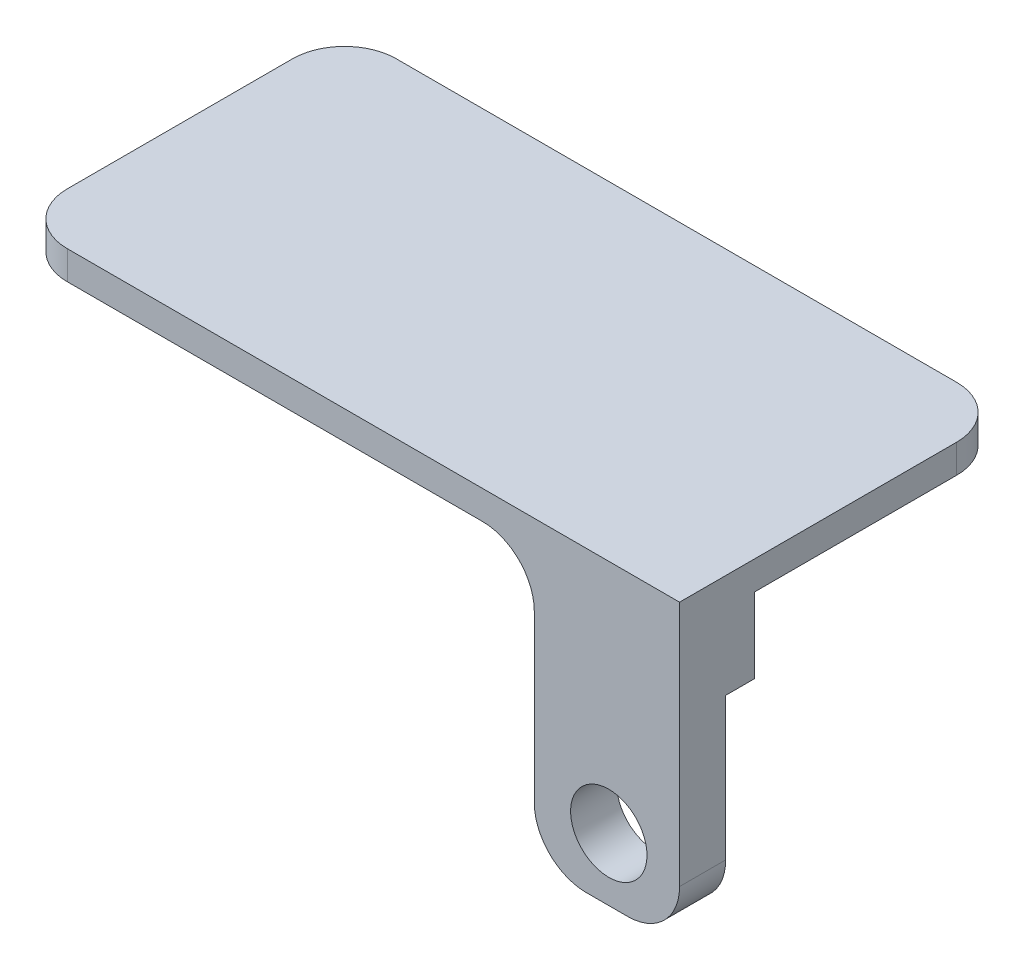
SolidWorks part; units mm, degrees
ref_plane "Front Plane" through (0, 0, 0) normal (0, 0, 1) x (1, 0, 0)
ref_plane "Top Plane" through (0, 0, 0) normal (0, 1, 0) x (1, 0, 0)
ref_plane "Right Plane" through (0, 0, 0) normal (1, 0, 0) x (0, 0, -1)
sketch "Sketch7" plane through (0, 0, 44.4916) normal (1, 0, 0) x (0, 1, 0)
  line L0 (57.2443, -80.0524) -> (75.9783, -80.0524)
  line L1 (83.2164, -82.8415) -> (83.2164, -107.3106)
  line L2 (75.9783, -80.0524) -> (75.9783, -82.8415)
  line L3 (85.9783, -75.6081) -> (57.2443, -75.6081)
  line L4 (57.2443, -80.0524) -> (57.2443, -75.6081)
  line L5 (83.2164, -107.3106) -> (85.9783, -107.3106)
  line L6 (85.9783, -107.3106) -> (85.9783, -75.6081)
  line L7 (75.9783, -82.8415) -> (83.2164, -82.8415)
  dimension "D1" = 10
extrude "Boss-Extrude6" add sketch "Sketch7" against normal blind 14
sketch "Sketch8" plane through (0, 0, -31.1164) normal (0, 0, 1) x (1, 0, 0)
  line L1 (-14, 75.9783) -> (0, 75.9783) construction
  circle A0 centre (-6.8193, 63.2783) radius 3.68
  dimension "D1" = 12.7
extrude "Cut-Extrude1" cut sketch "Sketch8" against normal blind 10
sketch "Sketch10" plane through (-14, 0, 0) normal (-1, 0, 0) x (0, 0, 1)
  line L1 (-31.1164, 85.9783) -> (-62.8189, 85.9783)
  line L2 (-31.1164, 85.9783) -> (-31.1164, 83.2164)
  line L3 (-31.1164, 83.2164) -> (-62.8189, 83.2164)
  line L4 (-62.8189, 85.9783) -> (-62.8189, 83.2164)
extrude "Boss-Extrude8" add sketch "Sketch10" along normal blind 50
fillet "Fillet2" radius 5 6 edges at (-64, 84.5973, -62.8189) (0, 84.5973, -62.8189) (0, 57.2443, -33.3386) (-14, 57.2443, -33.3386) (-64, 84.5973, -31.1164)
